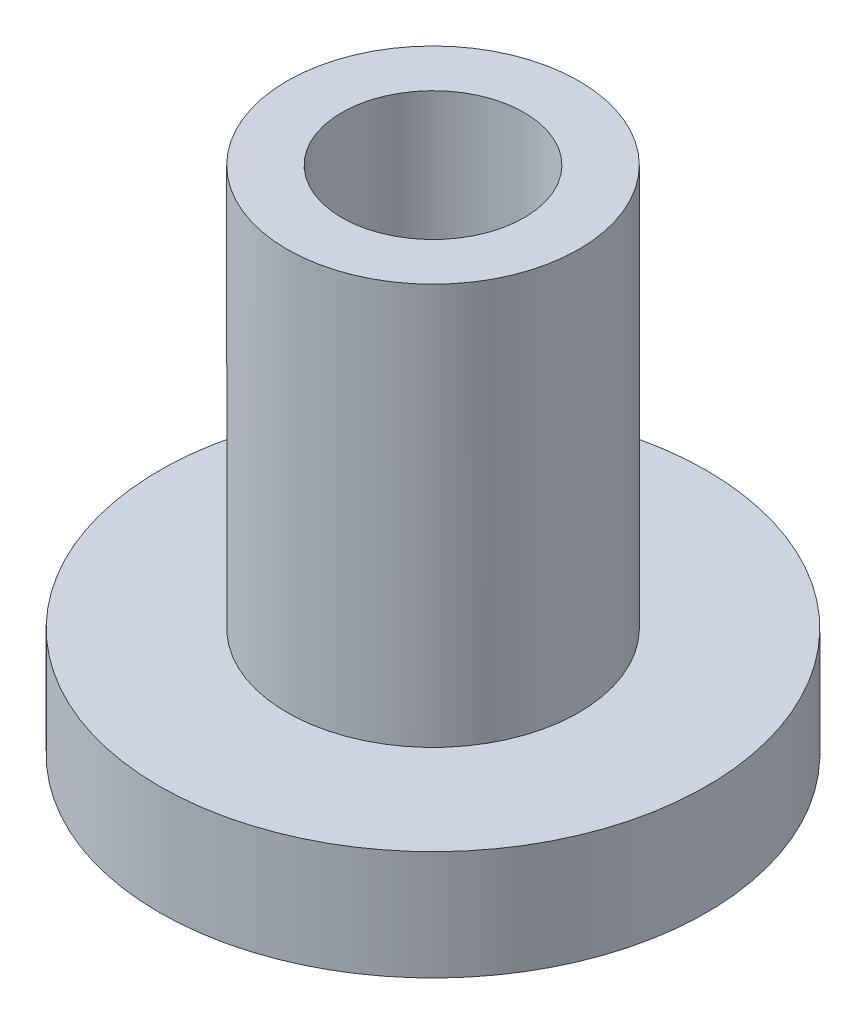
SolidWorks part; units mm, degrees
ref_plane "Plano frontal" through (0, 0, 0) normal (0, 0, 1) x (1, 0, 0)
ref_plane "Plano superior" through (0, 0, 0) normal (0, 1, 0) x (1, 0, 0)
ref_plane "Plano direito" through (0, 0, 0) normal (1, 0, 0) x (0, 0, -1)
sketch "Esboço1" plane through (0, 0, 0) normal (0, 1, 0) x (1, 0, 0)
  circle A0 centre (0, 0) radius 4
  dimension "D1" = 8
extrude "Ressalto-extrusão1" add sketch "Esboço1" along normal blind 11
sketch "Esboço3" plane through (0, 0, 0) normal (0, -1, 0) x (1, 0, 0)
  circle A0 centre (0, 0) radius 7.5
  dimension "D1" = 15
extrude "Ressalto-extrusão3" add sketch "Esboço3" along normal blind 3
sketch "Esboço6" plane through (0, 11, 0) normal (0, 1, 0) x (1, 0, 0)
  circle A0 centre (0, 0) radius 2.5
  dimension "D1" = 5
extrude "Corte-extrusão1" cut sketch "Esboço6" against normal through all
